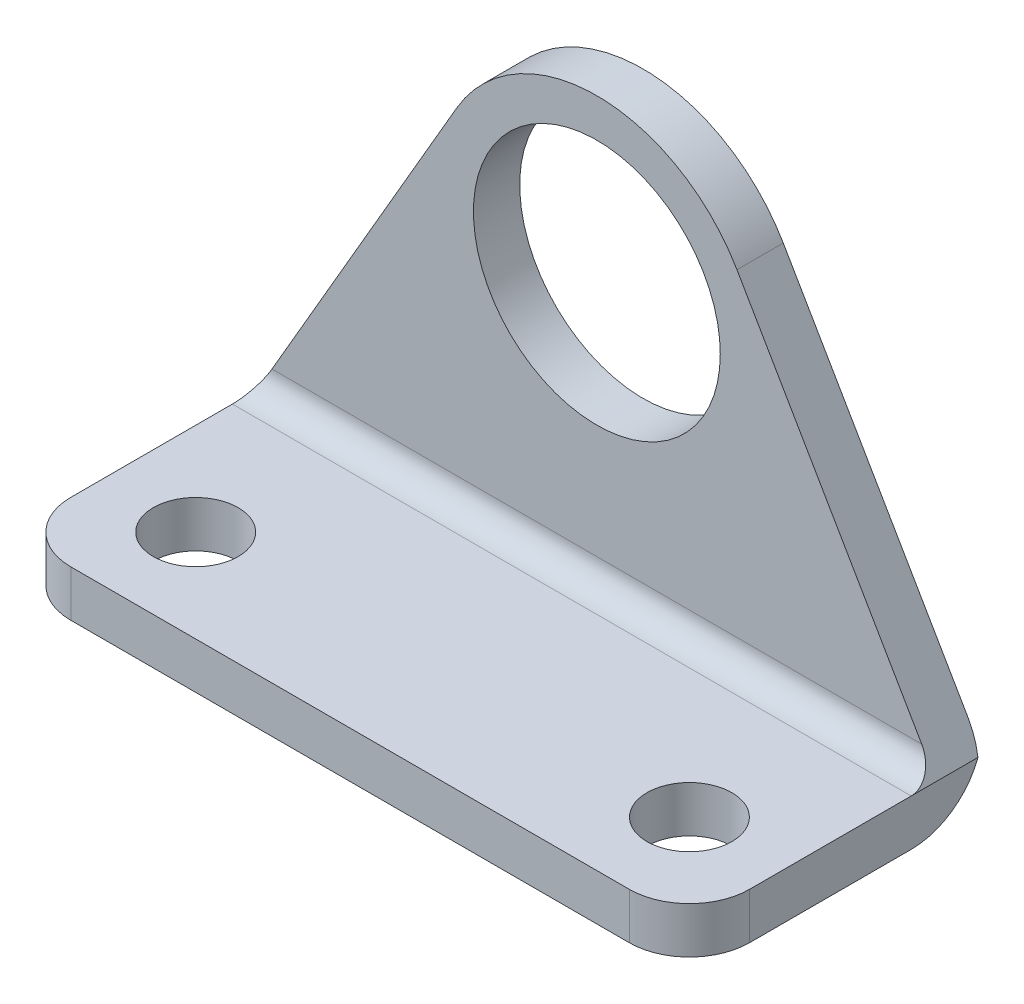
SolidWorks part; units mm, degrees
ref_plane "前视基准面" through (0, 0, 0) normal (0, 0, 1) x (1, 0, 0)
ref_plane "上视基准面" through (0, 0, 0) normal (0, 1, 0) x (1, 0, 0)
ref_plane "右视基准面" through (0, 0, 0) normal (1, 0, 0) x (0, 0, -1)
sketch "草图1" plane through (0, 0, 0) normal (0, 0, 1) x (1, 0, 0)
  line L0 (0, 0) -> (0, 20) construction
  line L1 (-22, 0) -> (22, 0) construction
  circle A0 centre (0, 20) radius 8
  circle A1 centre (0, 20) radius 10.5
  point P5 (16, 0)
  point P6 (0, 3)
  point P9 (0, 30.5)
  dimension "L" = 16
  dimension "U" = 21
  dimension "AE" = 44
  dimension "AF" = 32
  dimension "AH" = 20
  dimension "AT" = 3
sketch "草图2" plane through (0, 0, 0) normal (1, 0, 0) x (0, 0, -1)
  line L0 (0, 0) -> (-13, 0) construction
  line L1 (-13, 0) -> (-13, 3) construction
  point P3 (-10.25, 0)
  point P6 (-19, 0)
  point P7 (-38, 0)
  dimension "AL" = 13
  dimension "AP" = 5.5
  dimension "AQ" = 6
  dimension "AB" = 25
sketch "草图4" plane through (0, 0, 0) normal (1, 0, 0) x (0, 0, -1)
  line L0 (-19, 0) -> (-4.625, 0)
  line L1 (0, 4.625) -> (0, 30.5)
  line L3 (-19, 0) -> (-19, 3)
  line L4 (-19, 3) -> (-4.625, 3)
  line L5 (-3, 4.625) -> (-3, 30.5)
  line L6 (-3, 30.5) -> (0, 30.5)
  line L7 (0, 30.5) -> (0, 9.5) construction
  arc A0 (-4.625, 3) -> (-3, 4.625) centre (-4.625, 4.625) ccw
  arc A1 (-3, 8.9551) -> (-8.9551, 3) centre (-4.625, 4.625) ccw construction
  arc A2 (-4.625, 0) -> (0, 4.625) centre (-4.625, 4.625) ccw
  dimension "D1" = 3.25
extrude "凸台-拉伸1" add sketch "草图4" along normal up to vertex (22 mm away) from vertex at -22 starting at point (-22, 0, 0)
sketch "草图5" plane through (0, 0, 3) normal (0, 0, 1) x (1, 0, 0)
  line L0 (-9.0825, 25.2686) -> (-22, 3)
  line L1 (9.0825, 25.2686) -> (22, 3)
  line L2 (-22, 3) -> (-22, 31.5)
  line L3 (-22, 31.5) -> (22, 31.5)
  line L4 (22, 31.5) -> (22, 3)
  circle A0 centre (0, 20) radius 10.5 construction
  arc A1 (9.0825, 25.2686) -> (-9.0825, 25.2686) centre (0, 20) ccw
  dimension "D1" = 1
extrude "切除-拉伸1" cut sketch "草图5" against normal blind 10 and the other way up to surface other way up to face at (0, 1.5, 19)
sketch "草图6" plane through (0, 0, 3) normal (0, 0, 1) x (1, 0, 0)
  circle A0 centre (0, 20) radius 8 construction
  circle A1 centre (0, 20) radius 8
extrude "切除-拉伸2" cut sketch "草图6" against normal through all
sketch "草图7" plane through (0, 3, 0) normal (0, 1, 0) x (1, 0, 0)
  line L1 (0, 0) -> (0, -10.25) construction
  circle A0 centre (16, -13) radius 2.75
  circle A1 centre (-16, -13) radius 2.75
  point P2 (16, -10.25)
  point P11 (-16, -10.25)
extrude "切除-拉伸3" cut sketch "草图7" against normal through all
fillet "圆角1" radius 3.9 2 edges at (-22, 1.5, 19) (22, 1.5, 19)
equation "\"D1@草图4\" = \"AL@草图2\"*0.25"
equation "\"D1@圆角1\" = \"AL@草图2\"*0.3"
